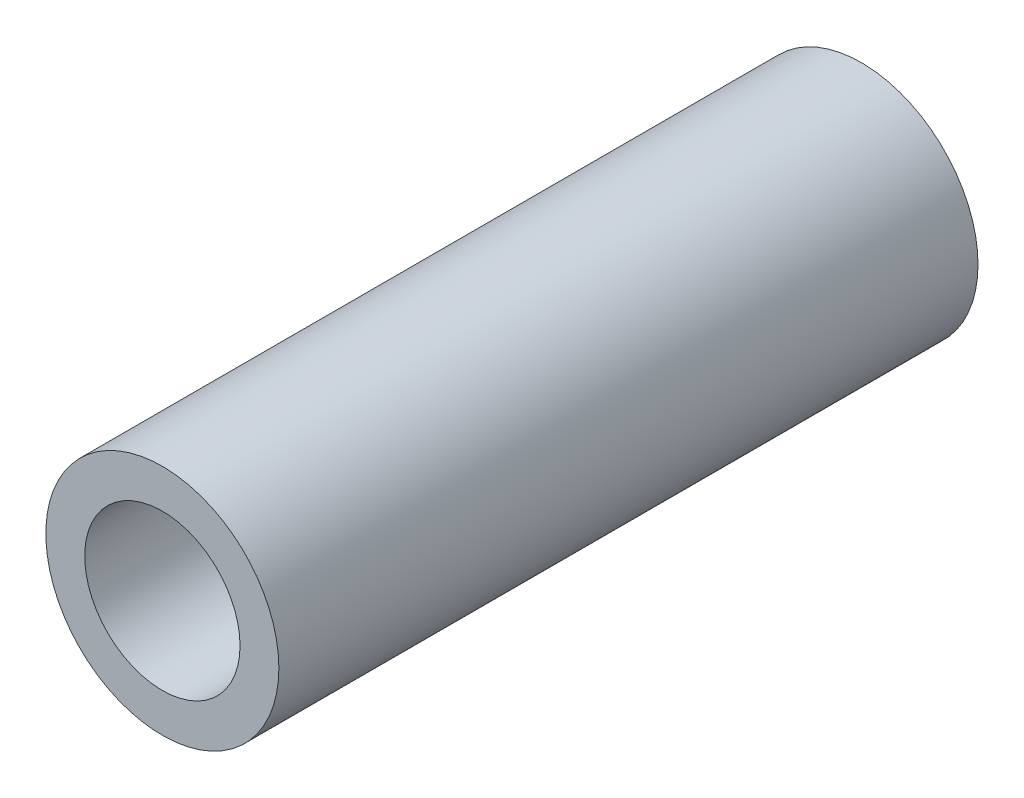
SolidWorks part; units mm, degrees
ref_plane "前视基准面" through (0, 0, 0) normal (0, 0, 1) x (1, 0, 0)
ref_plane "上视基准面" through (0, 0, 0) normal (0, 1, 0) x (1, 0, 0)
ref_plane "右视基准面" through (0, 0, 0) normal (1, 0, 0) x (0, 0, -1)
sketch "草图1" plane through (0, 0, 0) normal (0, 0, 1) x (1, 0, 0)
  circle A0 centre (0, 0) radius 2
  circle A1 centre (0, 0) radius 3
extrude "凸台-拉伸1" add sketch "草图1" along normal blind 18
